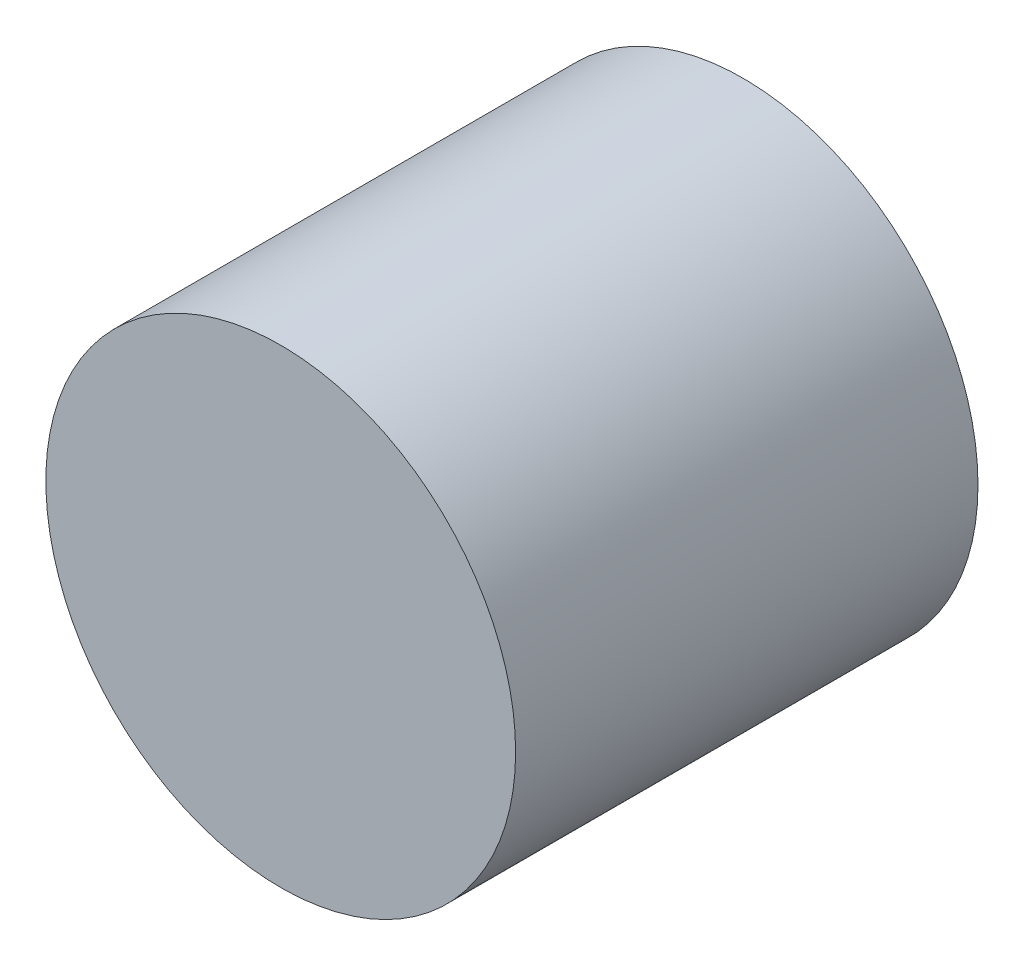
SolidWorks part; units mm, degrees
material "AISI 1020"
ref_plane "Plano frontal" through (0, 0, 0) normal (0, 0, 1) x (1, 0, 0)
ref_plane "Plano superior" through (0, 0, 0) normal (0, 1, 0) x (1, 0, 0)
ref_plane "Plano direito" through (0, 0, 0) normal (1, 0, 0) x (0, 0, -1)
sketch "Esboço1" plane through (0, 0, 0) normal (0, 0, 1) x (1, 0, 0)
  circle A0 centre (0, 0) radius 50.8
  dimension "D1" = 101.6
extrude "Ressalto-extrusão1" add sketch "Esboço1" along normal blind 100
sketch "Esboço2" plane through (0, 0, 0) normal (0, 0, -1) x (-1, 0, 0)
  circle A0 centre (0, 0) radius 49.8
  dimension "D1" = 99.6
extrude "Corte-extrusão1" cut sketch "Esboço2" against normal blind 99.6
